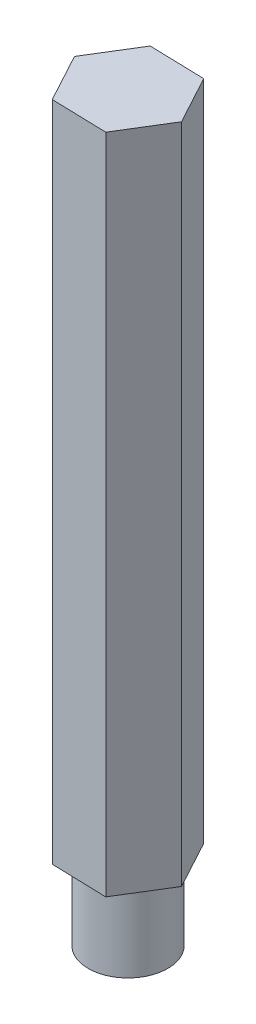
SolidWorks part; units mm, degrees
material "Brass"
ref_plane "Front Plane" through (0, 0, 0) normal (0, 0, 1) x (1, 0, 0)
ref_plane "Top Plane" through (0, 0, 0) normal (0, 1, 0) x (1, 0, 0)
ref_plane "Right Plane" through (0, 0, 0) normal (1, 0, 0) x (0, 0, -1)
sketch "Sketch1" plane through (0, 0, 0) normal (0, 1, 0) x (1, 0, 0)
  circle A0 centre (0, 0) radius 1.5
  dimension "D1" = 3
extrude "Boss-Extrude1" add sketch "Sketch1" along normal blind 3
sketch "Sketch2" plane through (0, 3, 0) normal (0, 1, 0) x (1, 0, 0)
  line L0 (0, 0) -> (-1.5, 0) construction
  line L1 (-0.9892, 1.828) -> (-2.0777, 0.0574)
  line L2 (-2.0777, 0.0574) -> (-1.0885, -1.7706)
  line L3 (-1.0885, -1.7706) -> (0.9892, -1.828)
  line L4 (0.9892, -1.828) -> (2.0777, -0.0574)
  line L5 (2.0777, -0.0574) -> (1.0885, 1.7706)
  line L6 (1.0885, 1.7706) -> (-0.9892, 1.828)
  circle A0 centre (0, 0) radius 1.8 construction
  circle A1 centre (0, 0) radius 1.5 construction
  dimension "D2" = 178.418
  dimension "D1" = 1.8
extrude "Boss-Extrude2" add sketch "Sketch2" along normal blind 25
